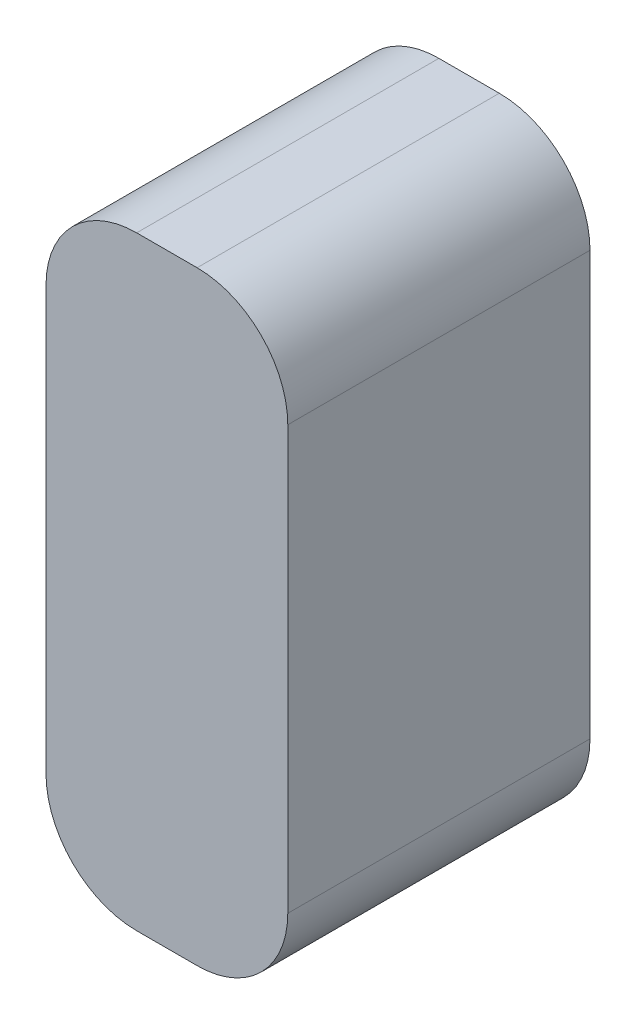
SolidWorks part; units mm, degrees
ref_plane "Front Plane" through (0, 0, 0) normal (0, 0, 1) x (1, 0, 0)
ref_plane "Top Plane" through (0, 0, 0) normal (0, 1, 0) x (1, 0, 0)
ref_plane "Right Plane" through (0, 0, 0) normal (1, 0, 0) x (0, 0, -1)
sketch "Sketch1" plane through (0, 0, 0) normal (0, 0, 1) x (1, 0, 0)
  line L0 (0, 260) -> (0, 375.7288) construction
  line L1 (-43, 260) -> (43, 260) construction
  line L3 (-4, 299) -> (4, 299)
  line L4 (-4, 299) -> (-4, 279)
  line L5 (-4, 279) -> (4, 279)
  line L6 (4, 299) -> (4, 279)
  dimension "D1" = 8
  dimension "D2" = 4
  dimension "D3" = 20
  dimension "D4" = 30
extrude "Boss-Extrude1" add sketch "Sketch1" along normal blind 10
fillet "Fillet1" radius 3 4 edges at (4, 279, 5) (-4, 279, 5) (4, 299, 5) (-4, 299, 5)
